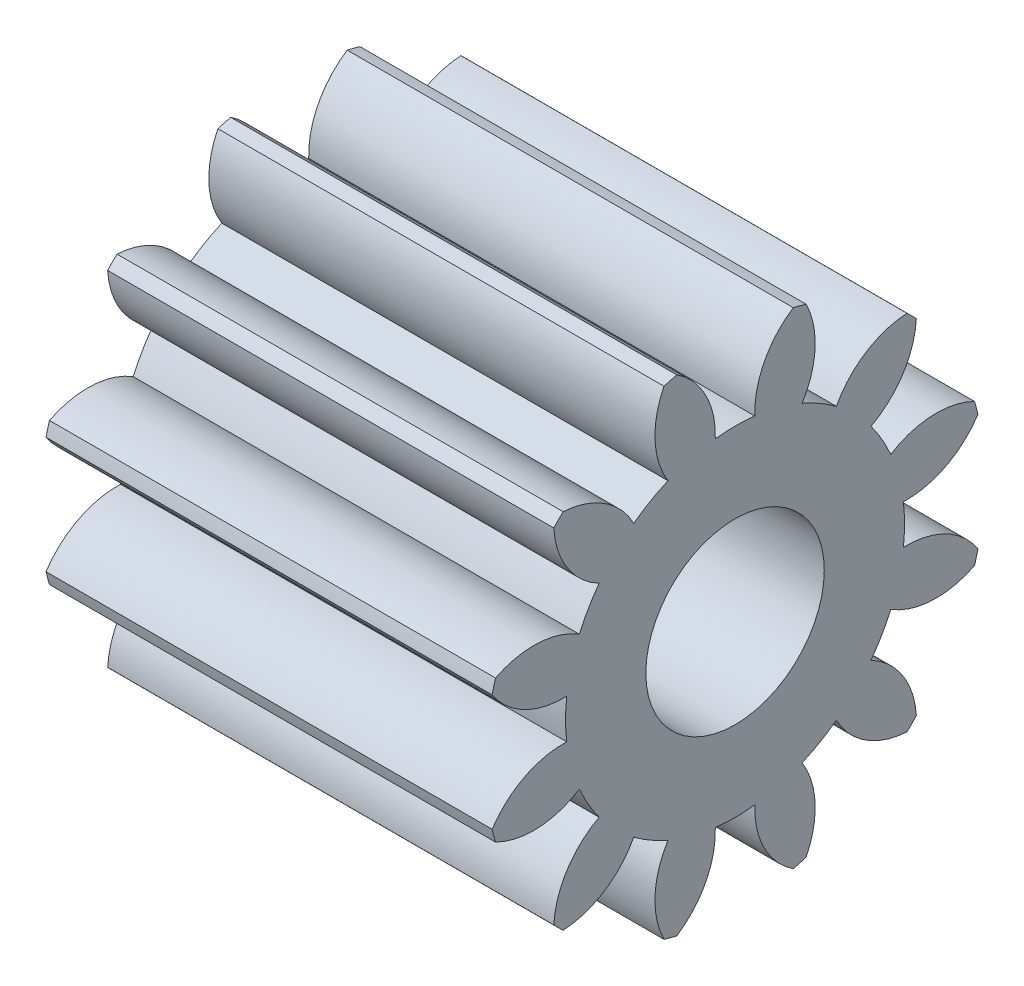
SolidWorks part; units mm, degrees
ref_plane "Plane1" through (0, 0, 0) normal (0, 0, 1) x (1, 0, 0)
ref_plane "Plane2" through (0, 0, 0) normal (0, 1, 0) x (1, 0, 0)
ref_plane "Plane3" through (0, 0, 0) normal (1, 0, 0) x (0, 0, -1)
sketch "HoldingSke" plane through (0, 0, 0) normal (0, 1, 0) x (1, 0, 0)
  line L0 (0, 0) -> (0.1223, -0.026)
  line L1 (-15, 0) -> (100, 0) construction
  line L2 (0, 0) -> (-2.1039, 2.3779)
  line L3 (0, 0) -> (-11.863, 4.5341)
  line L4 (0, 0) -> (8.4473, 1.7955)
  line L5 (0, 0) -> (-46.8476, -17.4728)
  line L6 (0, 0) -> (-82.8963, -55.9304)
  line L7 (-2.1039, 2.3779) -> (19.4211, 100.0338)
  line L8 (-76.2, 54.61) -> (-72.9, 54.61)
  line L9 (-71.009, 38.7566) -> (-53.1078, 45.2721)
  line L10 (-76.2, 71.12) -> (104.1128, 71.12)
  line L11 (0, 0) -> (-100, 0)
  line L12 (-76.2, 101.6) -> (-75.945, 101.6)
  line L13 (24.9733, 27.94) -> (52.9518, 28.4284)
  line L14 (24.9733, 27.94) -> (24.9743, 27.94)
  line L15 (24.9733, 27.94) -> (100.4006, 29.5858)
  line L16 (-63.627, -8) -> (-12.827, -8)
  circle A0 centre (0, 0) radius 20
  circle A1 centre (0, 0) radius 37.5
  circle A2 centre (0, 0) radius 37.5
  circle A3 centre (0, 0) radius 20
  dimension "MHD" = 75
  dimension "Hub_dia" = 75
  dimension "Bore" = 40
  dimension "MBD" = 40
  dimension "Num_teeth" = 12
  dimension "Pitch" = 0.125
  dimension "Overall_len" = 50
  dimension "Show_teeth" = 12
  dimension "Thickness" = 100
  dimension "OAL" = 100.0001
  dimension "T_dim" = 3.3
  dimension "Ap" = 20
  dimension "H" = 19.05
  dimension "Pitch_radius" = 180.3128
  dimension "Width" = 100
  dimension "Backlash" = 0.255
  dimension "Addendum_fac" = 1
  dimension "Dedendum_fac" = 1.25
  dimension "Clearance_fac" = 0.25
  dimension "Dedendum_add" = 0.001
  dimension "Module" = 8
sketch "BasProSke" plane through (0, 0, 0) normal (0, 1, 0) x (1, 0, 0)
  line L0 (-10, 0) -> (60, 0) construction
  line L1 (0, 0) -> (0, 56)
  line L2 (0, 0) -> (100, 0)
  line L3 (100, 0) -> (100, 56)
  line L4 (100, 56) -> (0, 56)
  dimension "Thickness" = 100
  dimension "Diameter" = 112
revolve "Base-Revolve" add sketch "BasProSke" angle 360 about L0
sketch "TooCutSke" plane through (0, 0, 0) normal (1, 0, 0) x (0, 0, -1)
  line L1 (0, 0) -> (0, 107) construction
  line L2 (0, 0) -> (-6.711, 47.5285) construction
  line L3 (0, 0) -> (-24.6634, 92.045) construction
  line L4 (-6.711, 47.5285) -> (-12.3317, 46.0225) construction
  arc A0 (4.4295, 37.7399) -> (-4.4295, 37.7399) centre (0, 0) ccw
  arc A1 (13.0788, 54.4774) -> (-13.0788, 54.4774) centre (0, 0) ccw
  circle A2 centre (0, 0) radius 48 construction
  circle A3 centre (0, 0) radius 45.1052 construction
  arc A4 (-4.4295, 37.7399) -> (-13.0788, 54.4774) centre (-23.6172, 38.428) ccw
  arc A5 (13.0788, 54.4774) -> (4.4295, 37.7399) centre (23.6172, 38.428) ccw
  dimension "Root_dia" = 75.998
  dimension "Overcut_dia" = 112.0508
  dimension "Pitch_dia" = 96
  dimension "Base_dia" = 90.2105
  dimension "Flank_rad" = 19.2
  dimension "Half_ang" = 15
  dimension "Half_CT" = 5.819
extrude "ToothCut" cut sketch "TooCutSke" along normal through all
fillet "Breaks" [suppressed] radius 0.16
fillet "RootFillets" [suppressed] radius 2.001
pattern_circular "TeethCuts" count 12 every 30 about axis through (-10, 0, 0) along (1, 0, 0) of "ToothCut", "RootFillets", "Breaks"
sketch "HubNeaOneSke" plane through (0, 0, 0) normal (-1, 0, 0) x (0, 0, 1)
  circle A0 centre (0, 0) radius 37.5
  dimension "Diameter" = 75
extrude "HubNearOne" [suppressed] add sketch "HubNeaOneSke" along normal blind 12.7001
sketch "HubNeaBotSke" plane through (0, 0, 0) normal (-1, 0, 0) x (0, 0, 1)
  circle A0 centre (0, 0) radius 37.5
  dimension "Diameter" = 75
extrude "HubNearBoth" [suppressed] add sketch "HubNeaBotSke" along normal blind 6.35
ref_plane "FarPln" through (100, 0, 0) normal (1, 0, 0) x (0, 0, -1)
sketch "HubFarSke" plane through (100, 0, 0) normal (1, 0, 0) x (0, 0, -1)
  circle A0 centre (0, 0) radius 37.5
  dimension "Diameter" = 75
extrude "HubFar" [suppressed] add sketch "HubFarSke" along normal blind 6.35
sketch "BorSke" plane through (0, 0, 0) normal (1, 0, 0) x (0, 0, -1)
  circle A0 centre (0, 0) radius 20
  dimension "Diameter" = 40
extrude "Bore" cut sketch "BorSke" along normal mid plane 200.0001
sketch "KeySke" plane through (0, 0, 0) normal (1, 0, 0) x (0, 0, -1)
  line L0 (-6, 0) -> (-6, 23.3)
  line L1 (-6, 23.3) -> (6, 23.3)
  line L2 (6, 23.3) -> (6, 0)
  line L3 (0, 0) -> (0, 34) construction
  line L4 (-6, 0) -> (6, 0)
  dimension "Offset" = 23.3
  dimension "Width" = 12
extrude "Keyway" [suppressed] cut sketch "KeySke" along normal mid plane 200.0001
pattern_circular "Keyway2" [suppressed] count 2 every 90 about axis through (-10, 0, 0) along (1, 0, 0)
equation "' \"Module@HoldingSke\" = 6.35"
equation "' \"Num_teeth@HoldingSke\" = 12"
equation "' \"Ap@HoldingSke\" =  20"
equation "' \"Ap@HoldingSke\" = 20"
equation "' \"Width@HoldingSke\" = 0.5 * 25.4"
equation "' \"Hub_dia@HoldingSke\"= 1 * 25.4"
equation "' \"Hub_dia@HoldingSke\" = 1 * 25.4"
equation "' \"Overall_len@HoldingSke\" = 1.0 * 25.4"
equation "' \"Bore@HoldingSke\" = 0.75 * 25.4"
equation "' \"T_dim@HoldingSke\" = 0.1 * 25.4"
equation "' \"Width@KeySke\" = 0.25 * 25.4"
equation "' \"Show_teeth@HoldingSke\" = 13"
equation "' \"Backlash@HoldingSke\" = 0.009 * 25.4"
equation "' \"Addendum_fac@HoldingSke\" = 1.0"
equation "' \"Dedendum_fac@HoldingSke\" = 1.25"
equation "' \"Dedendum_add@HoldingSke\" = 0.00005 * 25.4"
equation "' \"Clearance_fac@HoldingSke\" = 0.25"
equation "\"Pitch@HoldingSke\" = 1 / \"Module@HoldingSke\""
equation "\"Overcut_dia@TooCutSke\" = (\"Num_teeth@HoldingSke\" + 2 * \"Addendum_fac@HoldingSke\") / \"Pitch@HoldingSke\" + 0.002 * 25.4"
equation "\"Pitch_dia@TooCutSke\" = \"Num_teeth@HoldingSke\" / \"Pitch@HoldingSke\""
equation "\"Base_dia@TooCutSke\" = \"Num_teeth@HoldingSke\" / \"Pitch@HoldingSke\" * cos((\"Ap@HoldingSke\"  * 3.14159265 / 180))"
equation "\"Root_dia@TooCutSke\" = (\"Num_teeth@HoldingSke\" + 2) / \"Pitch@HoldingSke\" - 2 * (\"Addendum_fac@HoldingSke\" + \"Dedendum_fac@HoldingSke\") / \"Pitch@HoldingSke\" - \"Dedendum_add@HoldingSke\" * 2"
equation "\"Half_ang@TooCutSke\" = 180 / \"Num_teeth@HoldingSke\""
equation "\"Half_CT@TooCutSke\" = \"Num_teeth@HoldingSke\" / \"Pitch@HoldingSke\" * sin((3.14159265 / 2 / \"Num_teeth@HoldingSke\")) / 2 - 7 * \"Backlash@HoldingSke\" / 4"
equation "\"Flank_rad@TooCutSke\" = \"Num_teeth@HoldingSke\" / \"Pitch@HoldingSke\" / 5"
equation "\"Radius@RootFillets\" = \"Clearance_fac@HoldingSke\" / \"Pitch@HoldingSke\" + \"Dedendum_add@HoldingSke\""
equation "\"Break_rad@Breaks\" = 0.02 / \"Pitch@HoldingSke\""
equation "\"Thickness@HoldingSke\" = \"Width@HoldingSke\""
equation "\"OAL@HoldingSke\" = \"Thickness@HoldingSke\""
equation "\"MHD@HoldingSke\" = (\"Num_teeth@HoldingSke\" + 2) / \"Pitch@HoldingSke\" - 2 * (\"Addendum_fac@HoldingSke\" + \"Dedendum_fac@HoldingSke\")  / \"Pitch@HoldingSke\" - \"Dedendum_add@HoldingSke\" * 2"
equation "\"MBD@HoldingSke\" = (\"Num_teeth@HoldingSke\" + 2) / \"Pitch@HoldingSke\" - 2 * (\"Addendum_fac@HoldingSke\" + \"Dedendum_fac@HoldingSke\")  / \"Pitch@HoldingSke\" - \"Dedendum_add@HoldingSke\" * 2 - 0.002 * 25.4"
equation "\"MHD@HoldingSke\" = ((sgn( \"MHD@HoldingSke\" - \"Hub_dia@HoldingSke\" )-1)*( \"MHD@HoldingSke\" - \"Hub_dia@HoldingSke\" ))/-2+ \"Hub_dia@HoldingSke\""
equation "\"MBD@HoldingSke\" = ((sgn( \"MBD@HoldingSke\" - \"Bore@HoldingSke\" )-1)*( \"MBD@HoldingSke\" - \"Bore@HoldingSke\" ))/-2+ \"Bore@HoldingSke\""
equation "\"OAL@HoldingSke\" = ((sgn( \"OAL@HoldingSke\" - \"Overall_len@HoldingSke\" )+1)*( \"OAL@HoldingSke\" - \"Overall_len@HoldingSke\" ))/2 + \"Overall_len@HoldingSke\" + 0.000002 * 25.4"
equation "\"Num_teeth@TeethCuts\" = int( \"Show_teeth@HoldingSke\" ) + 1"
equation "\"Num_teeth@TeethCuts\" = ((sgn( \"Num_teeth@TeethCuts\" - \"Num_teeth@HoldingSke\" )-1)*( \"Num_teeth@TeethCuts\" - \"Num_teeth@HoldingSke\" ))/-2+ \"Num_teeth@HoldingSke\""
equation "\"Num_teeth@TeethCuts\" = ((sgn( \"Num_teeth@TeethCuts\" - 2.0)+1)*( \"Num_teeth@TeethCuts\" - 2.0))/2 +2.0"
equation "\"Angle@TeethCuts\" = 360.0 / \"Num_teeth@HoldingSke\""
equation "\"Diameter@BasProSke\" = (\"Num_teeth@HoldingSke\" + 2 * \"Addendum_fac@HoldingSke\") / \"Pitch@HoldingSke\""
equation "\"Thickness@BasProSke\"  = \"Thickness@HoldingSke\""
equation "' \"Fillet_rad@BasProSke\" =  \"Thickness@HoldingSke\" * 0.05"
equation "' \"Fillet_rad@BasProSke\" = \"Thickness@HoldingSke\" * 0.05"
equation "\"MHD@HoldingSke\" = ((sgn( \"MHD@HoldingSke\" - \"Root_dia@TooCutSke\" )-1)*( \"MHD@HoldingSke\" - \"Root_dia@TooCutSke\" ))/-2+ \"Root_dia@TooCutSke\""
equation "\"Diameter@HubNeaOneSke\" = \"MHD@HoldingSke\""
equation "\"Length@HubNearOne\" = \"OAL@HoldingSke\" - \"Thickness@BasProSke\""
equation "\"Diameter@HubNeaBotSke\" = \"MHD@HoldingSke\""
equation "\"Length@HubNearBoth\" = ( \"OAL@HoldingSke\" - \"Thickness@BasProSke\" ) / 2.0"
equation "\"Thickness@FarPln\" = \"Thickness@BasProSke\""
equation "\"Diameter@HubFarSke\" = \"MHD@HoldingSke\""
equation "\"Length@HubFar\" = ( \"OAL@HoldingSke\" - \"Thickness@BasProSke\" ) / 2.0"
equation "\"Diameter@BorSke\" = \"MBD@HoldingSke\""
equation "\"D1@Bore\" = \"OAL@HoldingSke\" * 2.0"
equation "\"D1@Keyway\" = \"OAL@HoldingSke\" * 2.0"
equation "\"Offset@KeySke\" = \"T_dim@HoldingSke\" + \"MBD@HoldingSke\" / 2.0"
